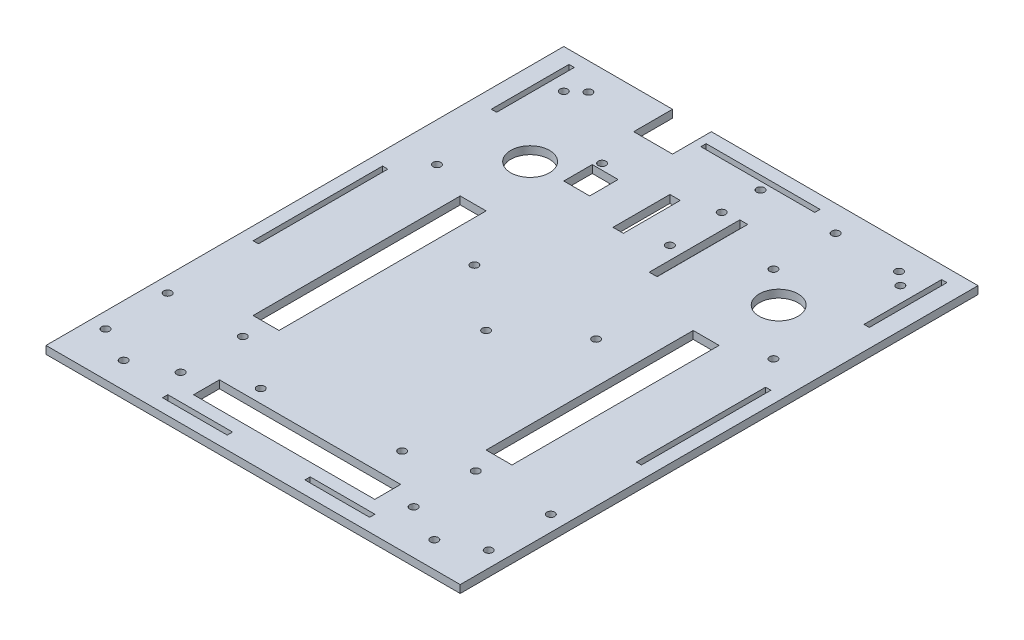
SolidWorks part; units mm, degrees
ref_plane "Front Plane" through (0, 0, 0) normal (0, 0, 1) x (1, 0, 0)
ref_plane "Top Plane" through (0, 0, 0) normal (0, 1, 0) x (1, 0, 0)
ref_plane "Right Plane" through (0, 0, 0) normal (1, 0, 0) x (0, 0, -1)
sketch "Sketch1" plane through (0, 0, 0) normal (0, 1, 0) x (1, 0, 0)
  line L1 (80, -100) -> (-80, -100)
  line L2 (80, -100) -> (80, 100)
  line L3 (80, 100) -> (-80, 100)
  line L4 (-80, -100) -> (-80, 100)
  line L5 (80, -100) -> (-80, 100) construction
  line L6 (80, 100) -> (-80, -100) construction
  point P0 (0, 0)
  dimension "D1" = 200
  dimension "D2" = 160
extrude "Boss-Extrude1" add sketch "Sketch1" along normal blind 3
sketch "Sketch2" plane through (0, 3, 0) normal (0, 1, 0) x (1, 0, 0)
  line L0 (-80, -100) -> (80, -100) construction
  line L1 (-80, 100) -> (-80, -100) construction
  line L2 (-3.268, 0) -> (0, 0) construction
  line L3 (0, 0) -> (0, -105.3922) construction
  line L4 (40, -92.95) -> (40, -95)
  line L5 (-40, -92.95) -> (-15, -92.95)
  line L6 (-40, -92.95) -> (-40, -95)
  line L7 (-40, -95) -> (-15, -95)
  line L8 (-15, -92.95) -> (-15, -95)
  line L9 (-40, -92.95) -> (-15, -95) construction
  line L10 (-40, -95) -> (-15, -92.95) construction
  line L11 (15, -92.95) -> (15, -95)
  line L12 (40, -95) -> (15, -95)
  line L13 (40, -92.95) -> (15, -92.95)
  line L14 (80, 100) -> (-80, 100) construction
  line L15 (75, -25) -> (72.95, -25)
  line L16 (-75, -25) -> (-72.95, -25)
  line L17 (-75, -25) -> (-75, 25)
  line L18 (-75, 25) -> (-72.95, 25)
  line L19 (-72.95, -25) -> (-72.95, 25)
  line L20 (-75, -25) -> (-72.95, 25) construction
  line L21 (-75, 25) -> (-72.95, -25) construction
  line L22 (72.95, -25) -> (72.95, 25)
  line L23 (75, -25) -> (75, 25)
  line L24 (75, 25) -> (72.95, 25)
  line L25 (73, 65) -> (70.95, 65)
  line L26 (-23, 85) -> (-38, 85)
  line L27 (-23, 85) -> (-23, 100)
  line L28 (-23, 100) -> (-38, 100)
  line L29 (-38, 85) -> (-38, 100)
  line L30 (-23, 85) -> (-38, 100) construction
  line L31 (-23, 100) -> (-38, 85) construction
  line L32 (24, 92.95) -> (-20, 92.95)
  line L33 (24, 92.95) -> (24, 95)
  line L34 (24, 95) -> (-20, 95)
  line L35 (-20, 92.95) -> (-20, 95)
  line L36 (24, 92.95) -> (-20, 95) construction
  line L37 (24, 95) -> (-20, 92.95) construction
  line L38 (-73, 95) -> (-70.95, 95)
  line L39 (-73, 95) -> (-73, 65)
  line L40 (-73, 65) -> (-70.95, 65)
  line L41 (-70.95, 95) -> (-70.95, 65)
  line L42 (-73, 95) -> (-70.95, 65) construction
  line L43 (-73, 65) -> (-70.95, 95) construction
  line L44 (70.95, 95) -> (70.95, 65)
  line L45 (73, 95) -> (73, 65)
  line L46 (73, 95) -> (70.95, 95)
  line L48 (-10, 49) -> (-6, 49)
  line L49 (-10, 49) -> (-10, 71)
  line L50 (-10, 71) -> (-6, 71)
  line L51 (-6, 49) -> (-6, 71)
  line L52 (-10, 49) -> (-6, 71) construction
  line L53 (-10, 71) -> (-6, 49) construction
  line L54 (15.05, 41) -> (12, 41)
  line L55 (15.05, 41) -> (15.05, 76)
  line L56 (15.05, 76) -> (12, 76)
  line L57 (12, 41) -> (12, 76)
  line L58 (15.05, 41) -> (12, 76) construction
  line L59 (15.05, 76) -> (12, 41) construction
  circle A0 centre (-60, -90) radius 1.5
  circle A1 centre (60, -90) radius 1.5
  circle A2 centre (0, -10) radius 1.5
  circle A3 centre (-65, 85) radius 1.5
  circle A4 centre (65, 85) radius 1.5
  point P14 (-27.5, -93.975)
  point P29 (-73.975, 0)
  point P38 (-30.5, 92.5)
  point P43 (2, 93.975)
  point P48 (-71.975, 80)
  point P57 (-8, 60)
  point P62 (13.525, 58.5)
  dimension "D1" = 3
  dimension "D4" = 3
  dimension "D10" = 3
  dimension "D11" = 15
  dimension "D12" = 15
  dimension "D2" = 10
  dimension "D3" = 20
  dimension "D5" = 90
  dimension "D6" = 40
  dimension "D7" = 2.05
  dimension "D8" = 5
  dimension "D9" = 25
  dimension "D13" = 50
  dimension "D14" = 75
  dimension "D15" = 2.05
  dimension "D16" = 5
  dimension "D17" = 23
  dimension "D18" = 15
  dimension "D19" = 15
  dimension "D20" = 5
  dimension "D21" = 2.05
  dimension "D22" = 44
  dimension "D23" = 2
  dimension "D24" = 30
  dimension "D25" = 5
  dimension "D26" = 2.05
  dimension "D27" = 7
  dimension "D28" = 29
  dimension "D29" = 22
  dimension "D30" = 4
  dimension "D31" = 10
  dimension "D32" = 3.05
  dimension "D33" = 24
  dimension "D34" = 35
  dimension "D35" = 12
extrude "Cut-Extrude1" cut sketch "Sketch2" against normal blind 3
sketch "Sketch3" plane through (0, 3, 0) normal (0, 1, 0) x (1, 0, 0)
  line L0 (-80, -100) -> (80, -100) construction
  line L1 (26.67, -78) -> (-26.67, -78)
  line L2 (26.67, -78) -> (26.67, 32)
  line L3 (26.67, 32) -> (-26.67, 32)
  line L4 (-26.67, -78) -> (-26.67, 32)
  line L5 (26.67, -78) -> (-26.67, 32) construction
  line L6 (26.67, 32) -> (-26.67, -78) construction
  line L7 (0, 0) -> (0, -100) construction
  circle A0 centre (-24.13, 9.6) radius 1.5
  circle A1 centre (24.13, 8.36) radius 1.5
  circle A2 centre (-24.13, -72.92) radius 1.5
  circle A3 centre (24.13, -66.57) radius 1.5
  point P0 (0, -23)
  dimension "D5" = 3
  dimension "D7" = 2.54
  dimension "D8" = 3
  dimension "D9" = 23.64
  dimension "D10" = 50.8
  dimension "D11" = 3
  dimension "D12" = 104.92
  dimension "D13" = 2.54
  dimension "D14" = 3
  dimension "D15" = 98.57
  dimension "D1" = 22
  dimension "D2" = 110
  dimension "D3" = 53.34
  dimension "D4" = 0
  dimension "D6" = 22.4
  dimension "D16" = 50.8
extrude "Cut-Extrude2" cut sketch "Sketch3" against normal through all contours A0 | A1 | A2 | A3
sketch "Sketch4" plane through (0, 3, 0) normal (0, 1, 0) x (1, 0, 0)
  line L0 (-80, -100) -> (80, -100) construction
  line L1 (-50, -50) -> (-40, -50)
  line L2 (-50, -50) -> (-50, 30)
  line L3 (-50, 30) -> (-40, 30)
  line L4 (-40, -50) -> (-40, 30)
  line L5 (-50, -50) -> (-40, 30) construction
  line L6 (-50, 30) -> (-40, -50) construction
  line L7 (-80, 100) -> (-80, -100) construction
  line L8 (0, 0) -> (0, -100) construction
  line L9 (50, -50) -> (40, -50)
  line L10 (40, -50) -> (40, 30)
  line L11 (50, -50) -> (50, 30)
  line L12 (50, 30) -> (40, 30)
  line L13 (-38, 100) -> (-80, 100) construction
  line L14 (35, -88) -> (-35, -88)
  line L15 (35, -88) -> (35, -78)
  line L16 (35, -78) -> (-35, -78)
  line L17 (-35, -88) -> (-35, -78)
  line L18 (35, -88) -> (-35, -78) construction
  line L19 (35, -78) -> (-35, -88) construction
  line L20 (-38, 100) -> (-80, 100) construction
  circle A0 centre (-48, 55) radius 7.5
  circle A1 centre (48, 55) radius 7.5
  circle A2 centre (-60, 89.5) radius 1.5
  circle A3 centre (60, 89.5) radius 1.5
  circle A4 centre (-65, 36) radius 1.5
  circle A5 centre (65, 36) radius 1.5
  point P0 (-45, -10)
  point P16 (0, -83)
  point P23 (-59, 100)
  dimension "D8" = 15
  dimension "D9" = 45
  dimension "D10" = 32
  dimension "D11" = 3
  dimension "D12" = 9
  dimension "D13" = 20
  dimension "D14" = 3
  dimension "D15" = 62.5
  dimension "D16" = 15
  dimension "D1" = 10
  dimension "D2" = 50
  dimension "D3" = 30
  dimension "D4" = 80
  dimension "D5" = 10
  dimension "D6" = 12
  dimension "D7" = 70
extrude "Cut-Extrude3" cut sketch "Sketch4" against normal blind 3
sketch "Sketch5" plane through (0, 3, 0) normal (0, 1, 0) x (1, 0, 0)
  line L0 (-80, -100) -> (80, -100) construction
  line L2 (-80, 100) -> (-80, -100) construction
  line L3 (-59.5, -54) -> (-59.5, -80) construction
  line L4 (0, 0) -> (0, -100) construction
  line L5 (80, 100) -> (-23, 100) construction
  line L8 (80, -100) -> (80, 100) construction
  circle A0 centre (-74, -83) radius 1.5
  circle A1 centre (-74, -59) radius 1.5
  circle A2 centre (-45, -83) radius 1.5
  circle A3 centre (-45, -59) radius 1.5
  circle A4 centre (45, -83) radius 1.5
  circle A5 centre (45, -59) radius 1.5
  circle A6 centre (74, -83) radius 1.5
  circle A7 centre (74, -59) radius 1.5
  circle A8 centre (6, 90) radius 1.5
  circle A9 centre (6, 75) radius 1.5
  circle A11 centre (35.005, 90) radius 1.5
  circle A12 centre (60, 89.5) radius 1.5 construction
  circle A13 centre (35, 66) radius 1.5
  dimension "D1" = 3
  dimension "D2" = 17
  dimension "D3" = 6
  dimension "D4" = 3
  dimension "D6" = 6
  dimension "D7" = 14.5
  dimension "D10" = 3
  dimension "D11" = 3
  dimension "D13" = 86
  dimension "D14" = 10
  dimension "D17" = 3
  dimension "D19" = 10
  dimension "D20" = 3
  dimension "D22" = 45
  dimension "D8" = 86
  dimension "D5" = 24
  dimension "D9" = 20
  dimension "D12" = 15
  dimension "D18" = 25
  dimension "D21" = 24
extrude "Cut-Extrude4" cut sketch "Sketch5" against normal blind 10
sketch "Sketch6" plane through (0, 3, 0) normal (0, 1, 0) x (1, 0, 0)
  line L0 (-80, 100) -> (-80, -100) construction
  line L1 (80, 100) -> (-23, 100) construction
  line L3 (9, 52) -> (-35, 52)
  line L4 (9, 52) -> (9, 70)
  line L5 (9, 70) -> (-35, 70)
  line L6 (-35, 52) -> (-35, 70)
  line L7 (9, 52) -> (-35, 70) construction
  line L8 (9, 70) -> (-35, 52) construction
  line L9 (-37, 55) -> (-25, 55)
  line L10 (-37, 55) -> (-37, 66)
  line L11 (-37, 66) -> (-25, 66)
  line L12 (-25, 55) -> (-25, 66)
  line L13 (-37, 55) -> (-25, 66) construction
  line L14 (-37, 66) -> (-25, 55) construction
  circle A0 centre (-33.5, 68.3) radius 1.5
  circle A1 centre (7, 54) radius 1.5
  point P5 (-13, 61)
  point P14 (-31, 60.5)
  dimension "D4" = 3
  dimension "D5" = 1.7
  dimension "D6" = 3
  dimension "D1" = 44
  dimension "D2" = 18
  dimension "D3" = 30
  dimension "D7" = 2
  dimension "D8" = 2
  dimension "D9" = 45
  dimension "D10" = 2
  dimension "D11" = 8.5
  dimension "D12" = 11
  dimension "D13" = 10
extrude "Cut-Extrude5" cut sketch "Sketch6" against normal blind 10 contours A0 | A1 | L9 L12 L11 L6
